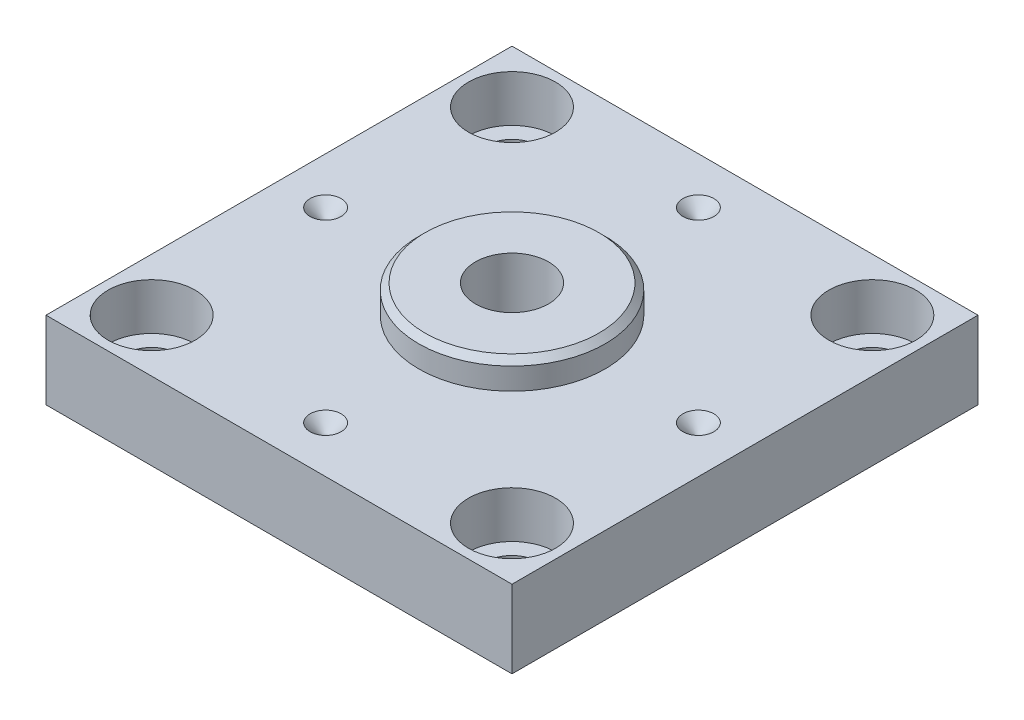
SolidWorks part; units mm, degrees
ref_plane "Front Plane" through (0, 0, 0) normal (0, 0, 1) x (1, 0, 0)
ref_plane "Top Plane" through (0, 0, 0) normal (0, 1, 0) x (1, 0, 0)
ref_plane "Right Plane" through (0, 0, 0) normal (1, 0, 0) x (0, 0, -1)
sketch "Sketch1" plane through (0, 0, 0) normal (0, 1, 0) x (1, 0, 0)
  line L1 (75, 75) -> (-75, 75)
  line L2 (75, 75) -> (75, -75)
  line L3 (75, -75) -> (-75, -75)
  line L4 (-75, 75) -> (-75, -75)
  line L5 (75, 75) -> (-75, -75) construction
  line L6 (75, -75) -> (-75, 75) construction
  point P0 (0, 0)
  dimension "D1" = 150
  dimension "D2" = 150
extrude "Boss-Extrude1" add sketch "Sketch1" along normal blind 25
sketch "Sketch2" plane through (0, 25, 0) normal (0, 1, 0) x (1, 0, 0)
  circle A0 centre (0, 0) radius 30
extrude "Boss-Extrude2" add sketch "Sketch2" along normal blind 9
chamfer "Chamfer1" distance 2 angle 45 1 edges at (0, 34, 30)
hole_wizard "M25x1.5 Tapped Hole1" positions "Sketch3" profile "Sketch4" tap size "M25x1.5" standard "DIN" end condition through all
sketch "Sketch3" plane through (0, 34, 0) normal (0, 1, 0) x (1, 0, 0)
  point P0 (0, 0)
  point P3 (0, 0)
sketch "Sketch4" plane through (0, 34, 0) normal (1, 0, 0) x (0, 0, 1)
  line L0 (0, 0) -> (0, 34)
  line L1 (0, 34) -> (11.75, 34)
  line L2 (11.75, 34) -> (11.75, 0)
  line L5 (11.75, 0) -> (0, 0)
  line L11 (0, -6.35) -> (0, 107.95) construction
  dimension "Thru Tap Drill Dia." = 23.5
  dimension "Thru Tap Drill Depth" = 34
cosmetic thread "Hole Thread1" parameters "D2"=25
cosmetic thread "Hole Thread2" parameters "D2"=25
hole_wizard "Hole1" positions "Sketch5" profile "Sketch6" legacy end condition through all
sketch "Sketch5" plane through (0, 25, 0) normal (0, 1, 0) x (1, 0, 0)
  point P0 (-58, -58)
  point P2 (58, -58)
  point P4 (58, 58)
  point P6 (-58, 58)
  point P13 (65.1184, 40.9932)
  point P14 (0, 0)
  point P15 (0, 0)
  point P17 (0, 0)
  point P18 (0, 0)
  point P19 (0, 0)
  dimension "D1" = 116
  dimension "D2" = 116
  dimension "D3" = 116
  dimension "D4" = 116
  dimension "D5" = 58
  dimension "D6" = 58
sketch "Sketch6" plane through (-58, 25, 58) normal (1, 0, 0) x (0, 0, 1)
  line L0 (0, 0) -> (0, 25)
  line L1 (0, 25) -> (8.5, 25)
  line L2 (8.5, 25) -> (8.5, 15)
  line L3 (8.5, 15) -> (14, 15)
  line L4 (14, 15) -> (14, 0)
  line L5 (14, 0) -> (0, 0)
  line L6 (0, 110) -> (0, -10) construction
  dimension "Diameter" = 17
  dimension "Depth" = 25
  dimension "C-Bore Diameter" = 28
  dimension "C-Bore Depth" = 15
sketch "Sketch7" plane through (0, 0, 0) normal (0, 0, 1) x (1, 0, 0)
  line L0 (-65, 25) -> (-60, 20)
  line L1 (-75, 25) -> (75, 25) construction
  line L3 (-60, 25) -> (-65, 25)
  line L4 (-60, 20) -> (-60, 25) construction
  line L5 (-60, 20) -> (-60, 25)
  dimension "D1" = 45
  dimension "D2" = 60
  dimension "D3" = 5
revolve "Cut-Revolve1" cut sketch "Sketch7" angle 360 about L4
pattern_circular "CirPattern1" count 4 over 360 about axis through (0, 0, 0) along (0, 1, 0) of "Cut-Revolve1"
